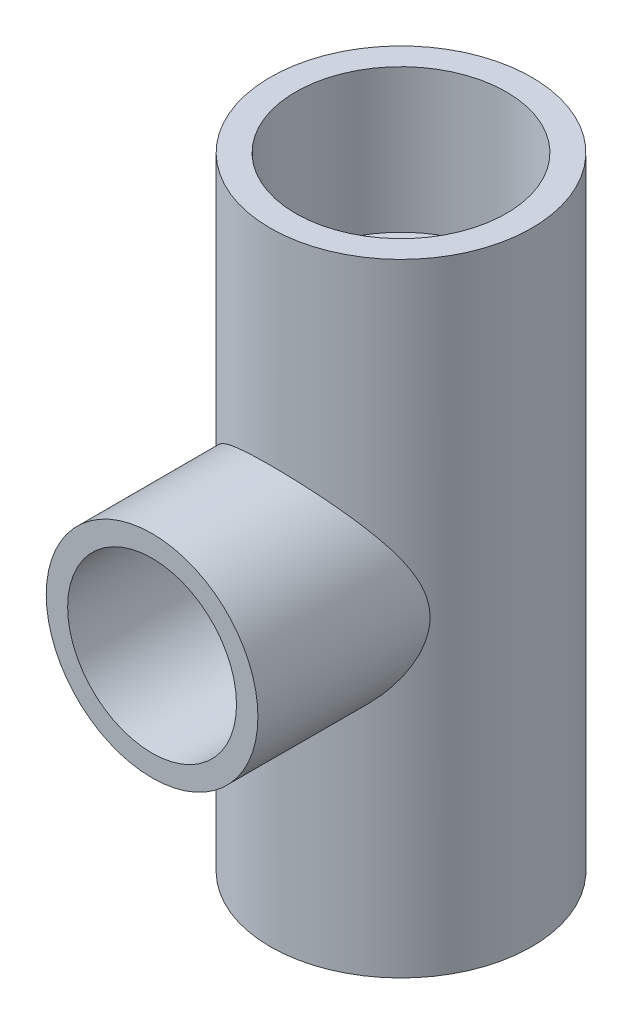
SolidWorks part; units mm, degrees
ref_plane "Front Plane" through (0, 0, 0) normal (0, 0, 1) x (1, 0, 0)
ref_plane "Top Plane" through (0, 0, 0) normal (0, 1, 0) x (1, 0, 0)
ref_plane "Right Plane" through (0, 0, 0) normal (1, 0, 0) x (0, 0, -1)
sketch "Sketch1" plane through (0, 0, 0) normal (0, 1, 0) x (1, 0, 0)
  circle A0 centre (0, 0) radius 656.5
  dimension "D1" = 1313
extrude "Boss-Extrude1" add sketch "Sketch1" along normal blind 3125
sketch "Sketch2" plane through (0, 0, 0) normal (0, 0, 1) x (1, 0, 0)
  line L0 (-656.5, 1562.5) -> (656.5, 1562.5) construction
  line L1 (-656.5, 3125) -> (-656.5, 0) construction
  line L2 (656.5, 0) -> (656.5, 3125) construction
  circle A0 centre (0, 1562.5) radius 531.5
  dimension "D1" = 1063
extrude "Boss-Extrude2" add sketch "Sketch2" along normal blind 1250
sketch "Sketch3" plane through (0, 0, 1250) normal (0, 0, 1) x (1, 0, 0)
  circle A0 centre (0, 1562.5) radius 424
  dimension "D1" = 848
extrude "Cut-Extrude1" cut sketch "Sketch3" against normal blind 690
sketch "Sketch4" plane through (0, 0, 560) normal (0, 0, 1) x (1, 0, 0)
  circle A0 centre (0, 1562.5) radius 311
  dimension "D1" = 622
extrude "Cut-Extrude2" cut sketch "Sketch4" against normal blind 560
sketch "Sketch5" plane through (0, 0, 0) normal (0, -1, 0) x (1, 0, 0)
  circle A0 centre (0, 0) radius 529
  dimension "D1" = 1058
extrude "Cut-Extrude3" cut sketch "Sketch5" against normal blind 720
sketch "Sketch6" plane through (0, 720, 0) normal (0, -1, 0) x (1, 0, 0)
  circle A0 centre (0, 0) radius 412
  dimension "D1" = 824
extrude "Cut-Extrude4" cut sketch "Sketch6" against normal through all
sketch "Sketch7" plane through (0, 3125, 0) normal (0, 1, 0) x (1, 0, 0)
  circle A0 centre (0, 0) radius 529
  dimension "D1" = 1058
extrude "Cut-Extrude5" cut sketch "Sketch7" against normal blind 720
